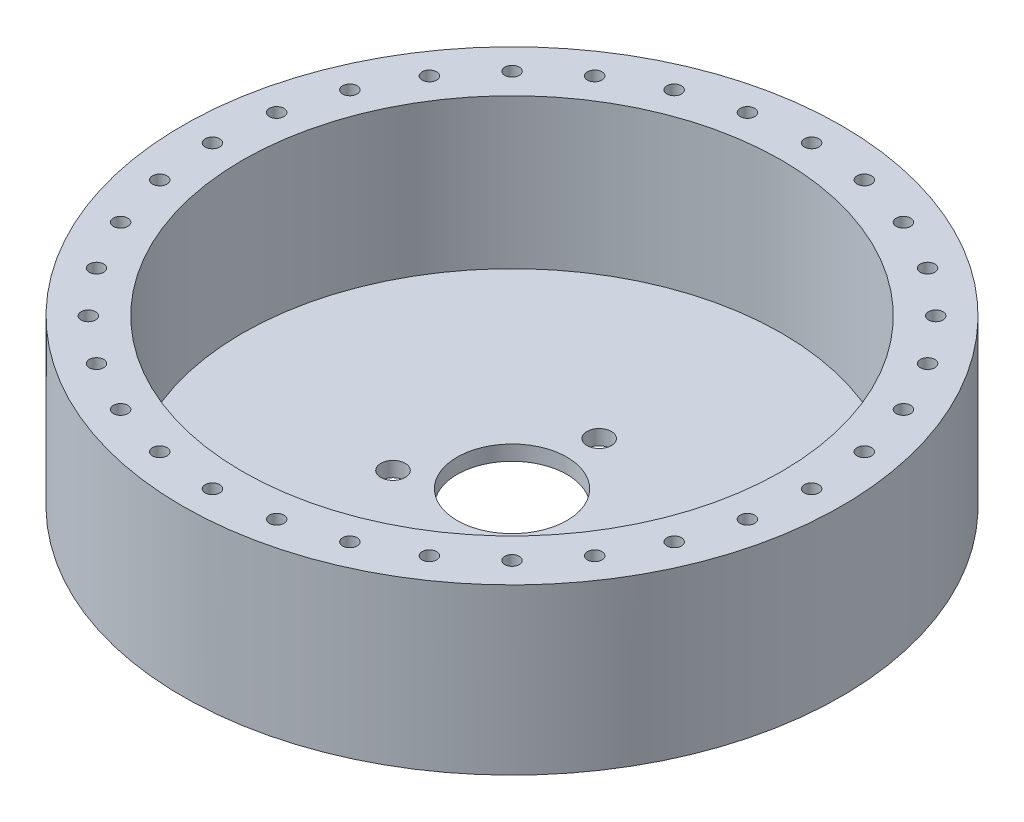
SolidWorks part; units mm, degrees
ref_plane "Front Plane" through (0, 0, 0) normal (0, 0, 1) x (1, 0, 0)
ref_plane "Top Plane" through (0, 0, 0) normal (0, 1, 0) x (1, 0, 0)
ref_plane "Right Plane" through (0, 0, 0) normal (1, 0, 0) x (0, 0, -1)
sketch "Sketch1" plane through (0, 0, 0) normal (0, 1, 0) x (1, 0, 0)
  circle A0 centre (0, 0) radius 66
  circle A1 centre (0, 0) radius 54
  dimension "D1" = 132
  dimension "D2" = 108
extrude "Boss-Extrude1" add sketch "Sketch1" along normal blind 30
sketch "Sketch2" plane through (0, 30, 0) normal (0, 1, 0) x (1, 0, 0)
  circle A0 centre (0, 0) radius 60 construction
  circle A1 centre (0, 60) radius 1.45
  circle A2 centre (11.7054, 58.8471) radius 1.45
  circle A3 centre (22.961, 55.4328) radius 1.45
  circle A4 centre (33.3342, 49.8882) radius 1.45
  circle A5 centre (42.4264, 42.4264) radius 1.45
  circle A6 centre (49.8882, 33.3342) radius 1.45
  circle A7 centre (55.4328, 22.961) radius 1.45
  circle A8 centre (58.8471, 11.7054) radius 1.45
  circle A9 centre (60, 0) radius 1.45
  circle A10 centre (58.8471, -11.7054) radius 1.45
  circle A11 centre (55.4328, -22.961) radius 1.45
  circle A12 centre (49.8882, -33.3342) radius 1.45
  circle A13 centre (42.4264, -42.4264) radius 1.45
  circle A14 centre (33.3342, -49.8882) radius 1.45
  circle A15 centre (22.961, -55.4328) radius 1.45
  circle A16 centre (11.7054, -58.8471) radius 1.45
  circle A17 centre (0, -60) radius 1.45
  circle A18 centre (-11.7054, -58.8471) radius 1.45
  circle A19 centre (-22.961, -55.4328) radius 1.45
  circle A20 centre (-33.3342, -49.8882) radius 1.45
  circle A21 centre (-42.4264, -42.4264) radius 1.45
  circle A22 centre (-49.8882, -33.3342) radius 1.45
  circle A23 centre (-55.4328, -22.961) radius 1.45
  circle A24 centre (-58.8471, -11.7054) radius 1.45
  circle A25 centre (-60, 0) radius 1.45
  circle A26 centre (-58.8471, 11.7054) radius 1.45
  circle A27 centre (-55.4328, 22.961) radius 1.45
  circle A28 centre (-49.8882, 33.3342) radius 1.45
  circle A29 centre (-42.4264, 42.4264) radius 1.45
  circle A30 centre (-33.3342, 49.8882) radius 1.45
  circle A31 centre (-22.961, 55.4328) radius 1.45
  circle A32 centre (-11.7054, 58.8471) radius 1.45
  point P70 (0, 0)
  dimension "D1" = 120
  dimension "D2" = 2.9
  dimension "D3" = 32
extrude "Cut-Extrude1" cut sketch "Sketch2" against normal blind 5
sketch "Sketch3" plane through (0, 0, 0) normal (0, -1, 0) x (1, 0, 0)
  circle A0 centre (0, 0) radius 66
  circle A1 centre (0, 0) radius 66 construction
extrude "Boss-Extrude2" add sketch "Sketch3" along normal blind 3
sketch "Sketch4" plane through (0, 0, 0) normal (0, 1, 0) x (1, 0, 0)
  line L0 (0, 0) -> (0, 17.45) construction
  line L1 (0, 0) -> (-15.1121, -8.725) construction
  line L2 (0, 0) -> (15.1121, -8.725) construction
  circle A0 centre (0, 0) radius 11
  circle A1 centre (0, 0) radius 17.45 construction
  circle A2 centre (0, 17.45) radius 2.45
  circle A3 centre (-15.1121, -8.725) radius 2.45
  circle A5 centre (15.1121, -8.725) radius 2.45
  dimension "D1" = 34.9
  dimension "D4" = 4.9
  dimension "D5" = 22
  dimension "D2" = 120
  dimension "D3" = 120
extrude "Cut-Extrude2" cut sketch "Sketch4" against normal through all
